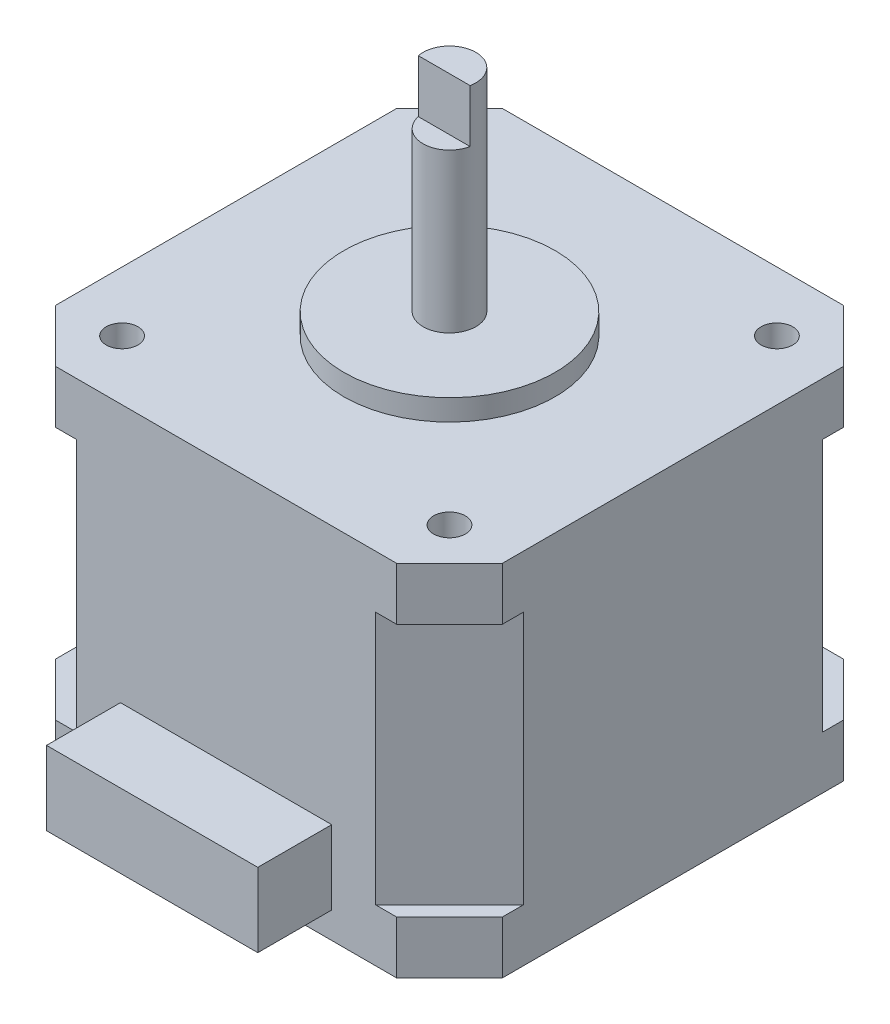
SolidWorks part; units mm, degrees
ref_plane "Front Plane" through (0, 0, 0) normal (0, 0, 1) x (1, 0, 0)
ref_plane "Top Plane" through (0, 0, 0) normal (0, 1, 0) x (1, 0, 0)
ref_plane "Right Plane" through (0, 0, 0) normal (1, 0, 0) x (0, 0, -1)
other "Configuration Table"
sketch "Sketch1" plane through (0, 0, 0) normal (0, 1, 0) x (1, 0, 0)
  line L1 (-21.15, -21.15) -> (21.15, -21.15)
  line L2 (-21.15, -21.15) -> (-21.15, 21.15)
  line L3 (-21.15, 21.15) -> (21.15, 21.15)
  line L4 (21.15, -21.15) -> (21.15, 21.15)
  line L5 (-21.15, -21.15) -> (21.15, 21.15) construction
  line L6 (-21.15, 21.15) -> (21.15, -21.15) construction
  point P0 (0, 0)
  dimension "D1" = 42.3
extrude "Boss-Extrude1" add sketch "Sketch1" along normal blind 5
chamfer "Chamfer1" distance 5 angle 45 4 edges at (21.15, 2.5, -21.15) (-21.15, 2.5, -21.15) (-21.15, 2.5, 21.15) (21.15, 2.5, 21.15)
sketch "Sketch2" plane through (0, 5, 0) normal (0, 1, 0) x (1, 0, 0)
  line L0 (-21.15, 14.15) -> (-14.15, 21.15)
  line L1 (-14.15, 21.15) -> (14.15, 21.15)
  line L2 (-21.15, 14.15) -> (-21.15, -14.15)
  line L3 (-14.15, -21.15) -> (14.15, -21.15)
  line L4 (21.15, 14.15) -> (21.15, -14.15)
  line L5 (-21.15, 21.15) -> (21.15, -21.15) construction
  line L6 (-21.15, -21.15) -> (21.15, 21.15) construction
  line L7 (14.15, 21.15) -> (21.15, 14.15)
  line L8 (14.15, -21.15) -> (21.15, -14.15)
  line L9 (-21.15, -14.15) -> (-14.15, -21.15)
  point P0 (0, 0)
  dimension "D1" = 42.3
extrude "Boss-Extrude2" add sketch "Sketch2" along normal blind 24
sketch "Sketch3" plane through (0, 29, 0) normal (0, 1, 0) x (1, 0, 0)
  line L1 (-21.15, 21.15) -> (21.15, 21.15)
  line L2 (-21.15, 21.15) -> (-21.15, -21.15)
  line L3 (-21.15, -21.15) -> (21.15, -21.15)
  line L4 (21.15, 21.15) -> (21.15, -21.15)
  line L5 (-21.15, 21.15) -> (21.15, -21.15) construction
  line L6 (-21.15, -21.15) -> (21.15, 21.15) construction
  point P0 (0, 0)
  dimension "D1" = 42.3
extrude "Boss-Extrude3" add sketch "Sketch3" along normal blind 5
chamfer "Chamfer2" distance 5 angle 45 4 edges at (21.15, 31.5, -21.15) (21.15, 31.5, 21.15) (-21.15, 31.5, 21.15) (-21.15, 31.5, -21.15)
sketch "Sketch4" plane through (0, 34, 0) normal (0, 1, 0) x (1, 0, 0)
  circle A0 centre (0, 0) radius 10
  dimension "D1" = 20
extrude "Boss-Extrude4" add sketch "Sketch4" along normal blind 2
sketch "Sketch5" plane through (0, 0, 21.15) normal (0, 0, 1) x (1, 0, 0)
  line L1 (-10, 2.5) -> (10, 2.5)
  line L2 (-10, 2.5) -> (-10, 9.5)
  line L3 (-10, 9.5) -> (10, 9.5)
  line L4 (10, 2.5) -> (10, 9.5)
  line L5 (-10, 2.5) -> (10, 9.5) construction
  line L6 (-10, 9.5) -> (10, 2.5) construction
  point P0 (0, 6)
  dimension "D1" = 7
  dimension "D2" = 20
  dimension "D3" = 6
extrude "Boss-Extrude5" add sketch "Sketch5" along normal blind 7
sketch "Sketch6" plane through (0, 36, 0) normal (0, 1, 0) x (1, 0, 0)
  circle A0 centre (0, 0) radius 2.5
extrude "Boss-Extrude6" add sketch "Sketch6" along normal blind 20
sketch "Sketch7" plane through (0, 56, 0) normal (0, 1, 0) x (1, 0, 0)
  line L0 (-2.4495, -0.5) -> (2.4495, -0.5)
  arc A0 (-2.4495, -0.5) -> (2.4495, -0.5) centre (0, 0) ccw
  circle A1 centre (0, 0) radius 2.5 construction
  arc A2 (2.4495, -0.5) -> (-2.4495, -0.5) centre (0, 0) ccw construction
  point P5 (0, 2.5)
extrude "Cut-Extrude1" cut sketch "Sketch7" against normal blind 5
sketch "Sketch8" plane through (0, 34, 0) normal (0, 1, 0) x (1, 0, 0)
  line L1 (-15.5, 15.5) -> (15.5, 15.5) construction
  line L2 (-15.5, 15.5) -> (-15.5, -15.5) construction
  line L3 (-15.5, -15.5) -> (15.5, -15.5) construction
  line L4 (15.5, 15.5) -> (15.5, -15.5) construction
  line L5 (-15.5, 15.5) -> (15.5, -15.5) construction
  line L6 (-15.5, -15.5) -> (15.5, 15.5) construction
  circle A0 centre (-15.5, 15.5) radius 1.5
  circle A1 centre (15.5, 15.5) radius 1.5
  circle A2 centre (15.5, -15.5) radius 1.5
  circle A3 centre (-15.5, -15.5) radius 1.5
  point P0 (0, 0)
  dimension "D2" = 3
  dimension "D1" = 31
extrude "Cut-Extrude2" cut sketch "Sketch8" against normal blind 5
